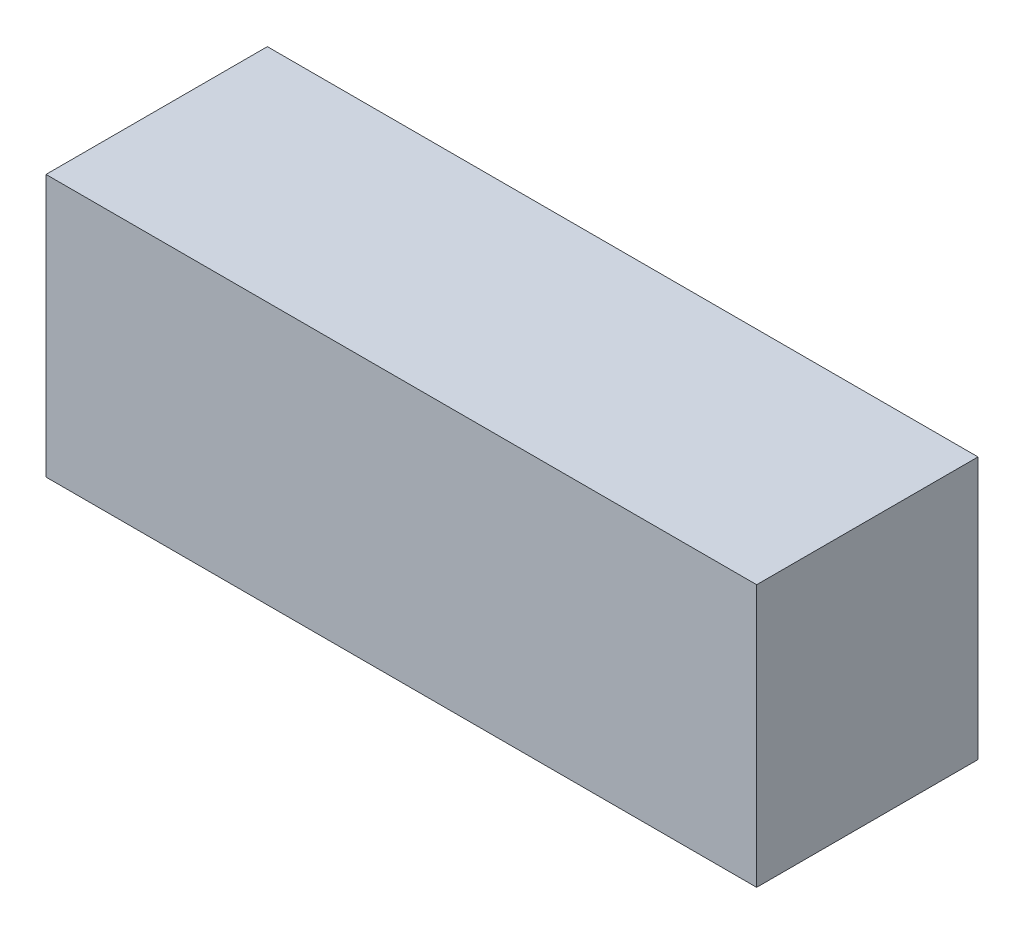
SolidWorks part; units mm, degrees
ref_plane "Front Plane" through (0, 0, 0) normal (0, 0, 1) x (1, 0, 0)
ref_plane "Top Plane" through (0, 0, 0) normal (0, 1, 0) x (1, 0, 0)
ref_plane "Right Plane" through (0, 0, 0) normal (1, 0, 0) x (0, 0, -1)
sketch "Sketch1" plane through (0, 0, 0) normal (0, 1, 0) x (1, 0, 0)
  line L1 (-12.7, 3.8) -> (-0.5, 3.8)
  line L2 (-12.7, 3.8) -> (-12.7, 0)
  line L3 (-12.7, 0) -> (-0.5, 0)
  line L4 (-0.5, 3.8) -> (-0.5, 0)
extrude "Boss-Extrude1" add sketch "Sketch1" along normal blind 4.5
